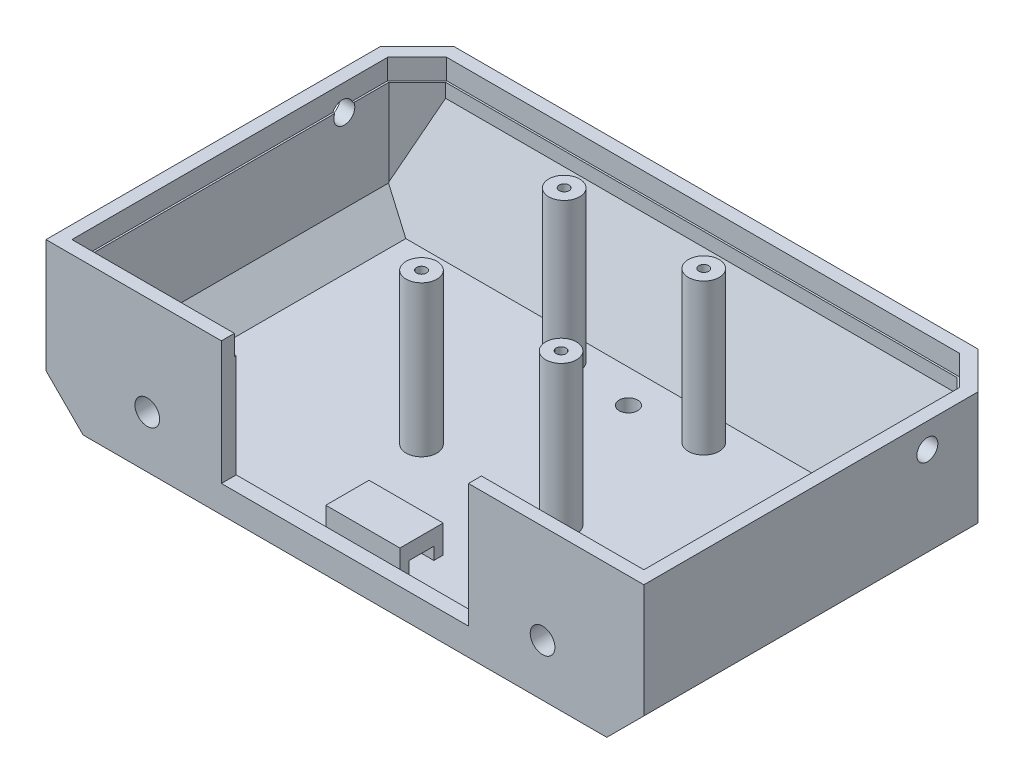
SolidWorks part; units mm, degrees
ref_plane "Front Plane" through (0, 0, 0) normal (0, 0, 1) x (1, 0, 0)
ref_plane "Top Plane" through (0, 0, 0) normal (0, 1, 0) x (1, 0, 0)
ref_plane "Right Plane" through (0, 0, 0) normal (1, 0, 0) x (0, 0, -1)
ref_plane "PZm28_4" through (0, -28.4, 0) normal (0, 1, 0) x (1, 0, 0)
sketch "Sketch1" plane through (0, -28.4, 0) normal (0, 1, 0) x (1, 0, 0)
  line L0 (-48.4, -11.9) -> (48.4, -11.9)
  line L1 (48.4, -11.9) -> (48.4, 42.2)
  line L2 (48.4, 42.2) -> (42.4, 48.2)
  line L3 (42.4, 48.2) -> (-42.4, 48.2)
  line L4 (-42.4, 48.2) -> (-48.4, 42.2)
  line L5 (-48.4, 42.2) -> (-48.4, -11.9)
extrude "Tray Block" add sketch "Sketch1" along normal blind 24.4
sketch "Sketch2" plane through (0, 0, 0) normal (1, 0, 0) x (0, 0, -1)
  line L0 (49.64, -6.32) -> (53.2, -6.32)
  line L1 (53.2, -6.32) -> (53.2, -32.08)
  line L2 (53.2, -32.08) -> (39.56, -32.08)
  line L3 (39.56, -32.08) -> (49.64, -6.32)
extrude "Lower Front Facet" cut sketch "Sketch2" against normal through all and the other way through all
sketch "Sketch3" plane through (0, 0, 0) normal (0, 0, 1) x (1, 0, 0)
  line L0 (-49.4, -21.4) -> (-49.4, -29.4)
  line L1 (-49.4, -29.4) -> (-41.4, -29.4)
  line L2 (-41.4, -29.4) -> (-49.4, -21.4)
extrude "Lower Side Facet L" cut sketch "Sketch3" against normal through all and the other way through all
sketch "Sketch4" plane through (0, 0, 0) normal (0, 0, 1) x (1, 0, 0)
  line L0 (49.4, -21.4) -> (49.4, -29.4)
  line L1 (49.4, -29.4) -> (41.4, -29.4)
  line L2 (41.4, -29.4) -> (49.4, -21.4)
extrude "Lower Side Facet R" cut sketch "Sketch4" against normal through all and the other way through all
shell "Shell" thickness 2.4
ref_plane "PZm7_3" through (0, -7.3, 0) normal (0, 1, 0) x (1, 0, 0)
sketch "Sketch5" plane through (0, -7.3, 0) normal (0, 1, 0) x (1, 0, 0)
  line L0 (-46.3, -9.8) -> (46.3, -9.8)
  line L1 (46.3, -9.8) -> (46.3, 41.3302)
  line L2 (46.3, 41.3302) -> (41.5302, 46.1)
  line L3 (41.5302, 46.1) -> (-41.5302, 46.1)
  line L4 (-41.5302, 46.1) -> (-46.3, 41.3302)
  line L5 (-46.3, 41.3302) -> (-46.3, -9.8)
extrude "Seam Rebate" cut sketch "Sketch5" along normal blind 4.3
ref_plane "PZm26_5" through (0, -26.5, 0) normal (0, 1, 0) x (1, 0, 0)
sketch "Sketch6" plane through (0, -26.5, 0) normal (0, 1, 0) x (1, 0, 0)
  circle A0 centre (-11.3, 11.8) radius 2.5
  circle A1 centre (-11.3, 34.9) radius 2.5
  circle A2 centre (11.3, 11.8) radius 2.5
  circle A3 centre (11.3, 34.9) radius 2.5
extrude "Board Pillars" add sketch "Sketch6" along normal blind 24.9
ref_plane "PZm9_6" through (0, -9.6, 0) normal (0, 1, 0) x (1, 0, 0)
sketch "Sketch7" plane through (0, -9.6, 0) normal (0, 1, 0) x (1, 0, 0)
  circle A0 centre (-11.3, 11.8) radius 0.8
  circle A1 centre (-11.3, 34.9) radius 0.8
  circle A2 centre (11.3, 11.8) radius 0.8
  circle A3 centre (11.3, 34.9) radius 0.8
extrude "Board Pilots" cut sketch "Sketch7" along normal blind 8.5
ref_plane "PY9" through (0, 0, 9) normal (0, 0, 1) x (1, 0, 0)
sketch "Sketch8" plane through (0, 0, 9) normal (0, 0, 1) x (1, 0, 0)
  line L0 (-20, -24) -> (20, -24)
  line L1 (20, -24) -> (20, -3)
  line L2 (20, -3) -> (-20, -3)
  line L3 (-20, -3) -> (-20, -24)
extrude "Cable Window" cut sketch "Sketch8" along normal blind 3.9
ref_plane "PY3_5" through (0, 0, 3.5) normal (0, 0, 1) x (1, 0, 0)
sketch "Sketch9" plane through (0, 0, 3.5) normal (0, 0, 1) x (1, 0, 0)
  circle A0 centre (-32, -20) radius 4
  circle A1 centre (32, -20) radius 4
extrude "Flange Bosses" add sketch "Sketch9" along normal blind 6.2
ref_plane "PY5_4" through (0, 0, 5.4) normal (0, 0, 1) x (1, 0, 0)
sketch "Sketch10" plane through (0, 0, 5.4) normal (0, 0, 1) x (1, 0, 0)
  circle A0 centre (-32, -20) radius 2
  circle A1 centre (32, -20) radius 2
extrude "Flange Insert Holes" cut sketch "Sketch10" along normal blind 7
ref_plane "PXm49_4" through (-49.4, 0, 0) normal (1, 0, 0) x (0, 0, -1)
sketch "Sketch11" plane through (-49.4, 0, 0) normal (1, 0, 0) x (0, 0, -1)
  circle A0 centre (34, -8) radius 1.7
extrude "Seam Screw Hole L" cut sketch "Sketch11" along normal blind 3.9
ref_plane "PX45_5" through (45.5, 0, 0) normal (1, 0, 0) x (0, 0, -1)
sketch "Sketch12" plane through (45.5, 0, 0) normal (1, 0, 0) x (0, 0, -1)
  circle A0 centre (34, -8) radius 1.7
extrude "Seam Screw Hole R" cut sketch "Sketch12" along normal blind 3.9
sketch "Sketch13" plane through (0, -26.5, 0) normal (0, 1, 0) x (1, 0, 0)
  line L0 (-6, -9) -> (6, -9)
  line L1 (6, -9) -> (6, -2)
  line L2 (6, -2) -> (-6, -2)
  line L3 (-6, -2) -> (-6, -9)
extrude "Bundle Tie Anchor" add sketch "Sketch13" along normal blind 5
ref_plane "PXm7" through (-7, 0, 0) normal (1, 0, 0) x (0, 0, -1)
sketch "Sketch14" plane through (-7, 0, 0) normal (1, 0, 0) x (0, 0, -1)
  line L0 (-7.5, -26) -> (-3.5, -26)
  line L1 (-3.5, -26) -> (-3.5, -24)
  line L2 (-3.5, -24) -> (-7.5, -24)
  line L3 (-7.5, -24) -> (-7.5, -26)
extrude "Bundle Tie Slot" cut sketch "Sketch14" along normal blind 14
ref_plane "PZm29_4" through (0, -29.4, 0) normal (0, 1, 0) x (1, 0, 0)
sketch "Sketch15" plane through (0, -29.4, 0) normal (0, 1, 0) x (1, 0, 0)
  circle A0 centre (0, 34) radius 1.5
extrude "Drain Hole" cut sketch "Sketch15" along normal blind 3.9
equation "\"BOARD_REAR\" = 86.0"
equation "\"BOARD_FRONT\" = 41.0"
equation "\"BOARD_END\" = 22.0"
equation "\"BOARD_ANGLED\" = 30.0"
equation "\"BOARD_DEPTH\" = 41.8431"
equation "\"PCB_T\" = 1.6"
equation "\"ABOVE_PCB\" = 14.0"
equation "\"BELOW_PCB\" = 6.0"
equation "\"MID_PARTS_H\" = 9.0"
equation "\"BOARD_HOLE_PILOT\" = 1.6"
equation "\"J2_X\" = 19.0"
equation "\"DUPONT_DROP\" = 14.0"
equation "\"BEND_R\" = 5.0"
equation "\"BOARD_GAP\" = 3.0"
equation "\"TOF_FOV\" = 25.0"
equation "\"TOF_MARGIN_DEG\" = 5.0"
equation "\"TOF_WIN_MARGIN\" = 1.0"
equation "\"TOF_Z\" = 9.0"
equation "\"TOF_SIDE_BEARING\" = 90.0"
equation "\"TOF_CONE_LEN\" = 70.0"
equation "\"CAM_W\" = 29.2"
equation "\"CAM_H\" = 28.2"
equation "\"CAM_D\" = 12.35"
equation "\"CAM_FRONT_Y\" = 43.0"
equation "\"CAM_BOTTOM_Z\" = 17.0"
equation "\"CAM_LENS_UP\" = 11.6"
equation "\"CAM_LENS_OPEN\" = 9.6"
equation "\"CAM_HFOV\" = 53.5"
equation "\"CAM_VFOV\" = 41.41"
equation "\"CAM_FOV_MARGIN\" = 3.0"
equation "\"CAM_FIT\" = 0.3"
equation "\"RIBBON_W\" = 16.0"
equation "\"RIBBON_T\" = 0.3"
equation "\"RIBBON_LEN\" = 150.0"
equation "\"RIBBON_EXIT_Y\" = 35.0"
equation "\"WALL\" = 2.4"
equation "\"HEAD_X\" = 48.4"
equation "\"HEAD_REAR_Y\" = -11.9"
equation "\"CAM_FOAM\" = 2.8"
equation "\"HEAD_FRONT_Y\" = 48.2"
equation "\"HEAD_TOP_Z\" = 50.6"
equation "\"HEAD_BOT_Z\" = -28.4"
equation "\"HEAD_SPLIT_Z\" = -4.0"
equation "\"SKIRT_T\" = 1.2"
equation "\"SKIRT_H\" = 3.0"
equation "\"SKIRT_FIT\" = 0.3"
equation "\"VISOR\" = 7.8"
equation "\"VISOR_Z\" = 40.0"
equation "\"ROOF_SLOPE_Y\" = 40.0"
equation "\"ROOF_CHAMFER\" = 10.0"
equation "\"REAR_CHAMFER\" = 10.0"
equation "\"CORNER_CHAMFER\" = 6.0"
equation "\"LOWER_SIDE_FACET\" = 6.0"
equation "\"LIGHTBAR_DEPTH\" = 1.0"
equation "\"HOOD_Z\" = 14.0"
equation "\"HOOD_L\" = 6.0"
equation "\"SIDE_HOOD_L\" = 4.0"
equation "\"INSERT_M3_D\" = 4.0"
equation "\"INSERT_M3_L\" = 6.0"
equation "\"M3_CLEAR\" = 3.4"
equation "\"M2_PILOT\" = 1.6"
equation "\"M25_PILOT\" = 2.2"
equation "\"BOX_X\" = 72.4"
equation "\"BOX_FRONT_Y\" = -11.9"
equation "\"BOX_REAR_Y\" = -154.4"
equation "\"BOX_BOT_Z\" = -28.4"
equation "\"BOX_TOP_Z\" = 10.0"
equation "\"LID_T\" = 2.4"
equation "\"LID_SKIRT\" = 1.6"
equation "\"LID_TONGUE_H\" = 3.0"
equation "\"LID_FIT\" = 0.3"
equation "\"GNSS_WIN_T\" = 1.2"
equation "\"DIVIDER_Y\" = -86.0"
equation "\"PI_X0\" = -40.0"
equation "\"PI_X1\" = 45.0"
equation "\"PI_Y1\" = -26.3"
equation "\"PI_Y0\" = -82.3"
equation "\"PI_STANDOFF\" = 8.0"
equation "\"ESP_X0\" = -46.0"
equation "\"ESP_Y0\" = -149.0"
equation "\"ESP_L\" = 75.0"
equation "\"ESP_W\" = 52.0"
equation "\"ESP_STANDOFF\" = 12.0"
equation "\"VENT_UPSTAND\" = 3.0"
equation "\"TUBE_D\" = 22.2"
equation "\"TUBE_LINER\" = 1.0"
equation "\"MOUNT_Y\" = -70.0"
equation "\"RAIL_W\" = 30.0"
equation "\"RAIL_W2\" = 38.0"
equation "\"RAIL_H\" = 6.0"
equation "\"SLIDE\" = 0.3"
equation "\"STOP_T\" = 6.0"
equation "\"CLAMP_W\" = 40.0"
equation "\"CLAMP_HALF\" = 20.0"
equation "\"CLAMP_DROP\" = 12.0"
equation "\"CAP_T\" = 12.0"
equation "\"CLAMP_BOLT_OFF\" = 16.6"
equation "\"M5_INSERT_D\" = 6.4"
equation "\"M5_CLEAR\" = 5.5"
equation "\"LOCK_D\" = 3.3"
equation "\"POD_TILT_DEG\" = 0.0"
equation "\"PRINT_LIMIT\" = 180.0"
